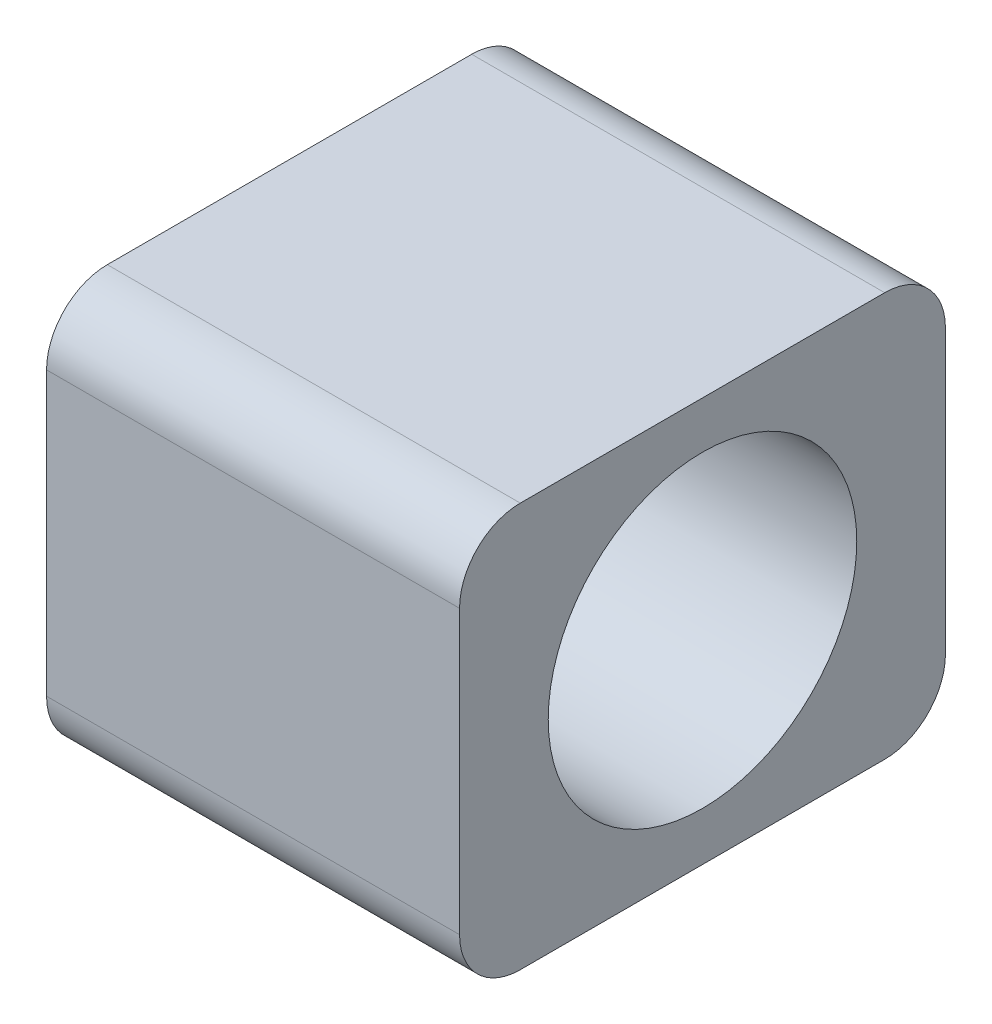
SolidWorks part; units mm, degrees
ref_plane "Front Plane" through (0, 0, 0) normal (0, 0, 1) x (1, 0, 0)
ref_plane "Top Plane" through (0, 0, 0) normal (0, 1, 0) x (1, 0, 0)
ref_plane "Right Plane" through (0, 0, 0) normal (1, 0, 0) x (0, 0, -1)
sketch "Sketch1" plane through (0, 0, 0) normal (1, 0, 0) x (0, 0, -1)
  line L0 (-15, -16.7) -> (15, -16.7)
  line L1 (20, -11.7) -> (20, 11.569)
  line L2 (15, 16.569) -> (-15, 16.569)
  line L3 (-20, 11.569) -> (-20, -11.7)
  arc A0 (15, -16.7) -> (20, -11.7) centre (15, -11.7) ccw
  arc A1 (20, 11.569) -> (15, 16.569) centre (15, 11.569) ccw
  arc A2 (-15, 16.569) -> (-20, 11.569) centre (-15, 11.569) ccw
  arc A3 (-20, -11.7) -> (-15, -16.7) centre (-15, -11.7) ccw
  circle A4 centre (0, 0) radius 12.7
extrude "Boss-Extrude1" add sketch "Sketch1" along normal mid plane 34
